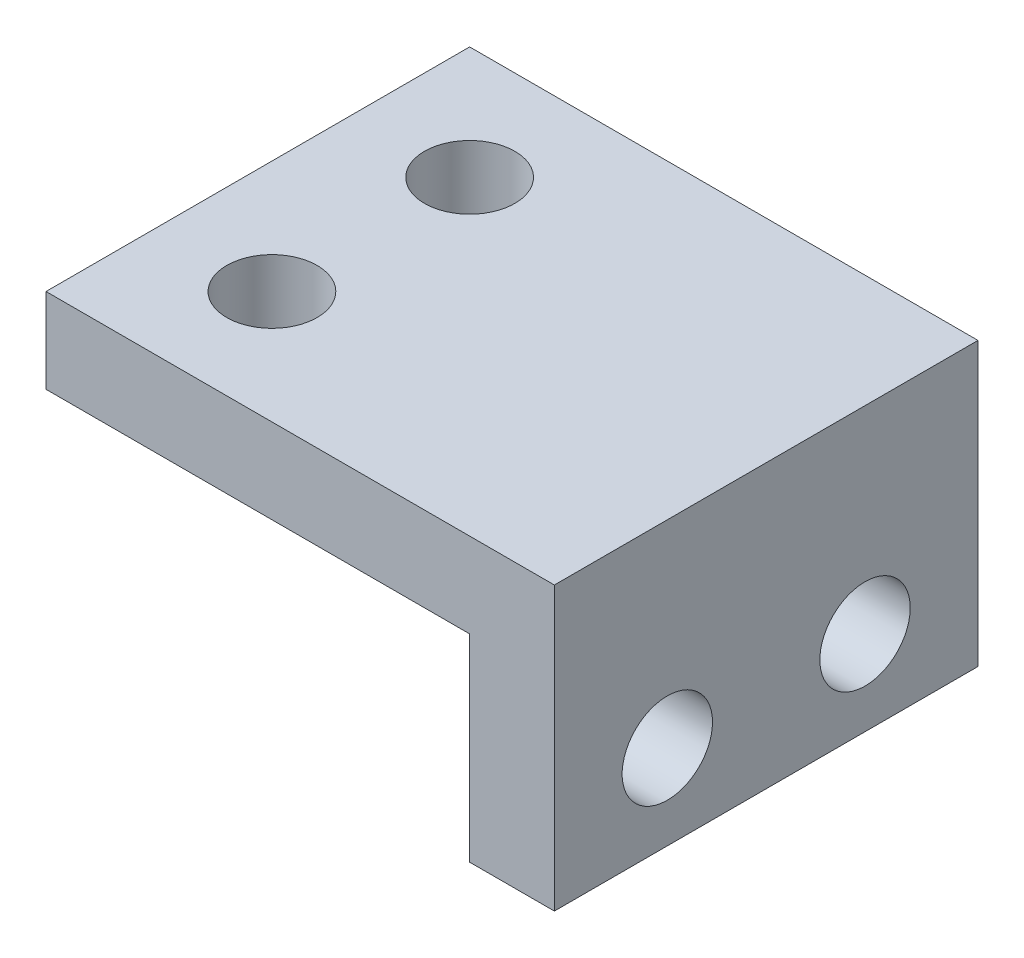
SolidWorks part; units mm, degrees
ref_plane "Front Plane" through (0, 0, 0) normal (0, 0, 1) x (1, 0, 0)
ref_plane "Top Plane" through (0, 0, 0) normal (0, 1, 0) x (1, 0, 0)
ref_plane "Right Plane" through (0, 0, 0) normal (1, 0, 0) x (0, 0, -1)
sketch "Sketch1" plane through (0, 0, 0) normal (0, 0, 1) x (1, 0, 0)
  line L0 (0, 0) -> (-15, 0)
  line L1 (0, 0) -> (0, -7)
  line L2 (0, -7) -> (3, -7)
  line L3 (3, -7) -> (3, 3)
  line L4 (3, 3) -> (-15, 3)
  line L5 (-15, 3) -> (-15, 0)
  dimension "D1" = 7
  dimension "D2" = 15
  dimension "D3" = 3
  dimension "D4" = 3
extrude "Boss-Extrude1" add sketch "Sketch1" along normal mid plane 15
sketch "Sketch2" plane through (0, 3, 0) normal (0, 1, 0) x (1, 0, 0)
  line L0 (-15, -7.5) -> (-15, 7.5) construction
  line L1 (3, -7.5) -> (-15, -7.5) construction
  line L2 (3, 7.5) -> (-15, 7.5) construction
  circle A0 centre (-11, 3.5) radius 1.6
  circle A1 centre (-11, -3.5) radius 1.6
  dimension "D1" = 3.2
  dimension "D2" = 3.2
  dimension "D3" = 4
  dimension "D4" = 4
  dimension "D5" = 4
  dimension "D6" = 4
extrude "Cut-Extrude1" cut sketch "Sketch2" against normal blind 15
sketch "Sketch3" plane through (3, 0, 0) normal (1, 0, 0) x (0, 0, -1)
  line L0 (7.5, -7) -> (7.5, 3) construction
  line L1 (-7.5, -7) -> (7.5, -7) construction
  line L2 (-7.5, -7) -> (-7.5, 3) construction
  circle A0 centre (-3.5, -4) radius 1.6
  circle A1 centre (3.5, -4) radius 1.6
  dimension "D1" = 3.2
  dimension "D2" = 3.2
  dimension "D3" = 4
  dimension "D4" = 3
  dimension "D5" = 3
  dimension "D6" = 4
extrude "Cut-Extrude2" cut sketch "Sketch3" against normal blind 15
